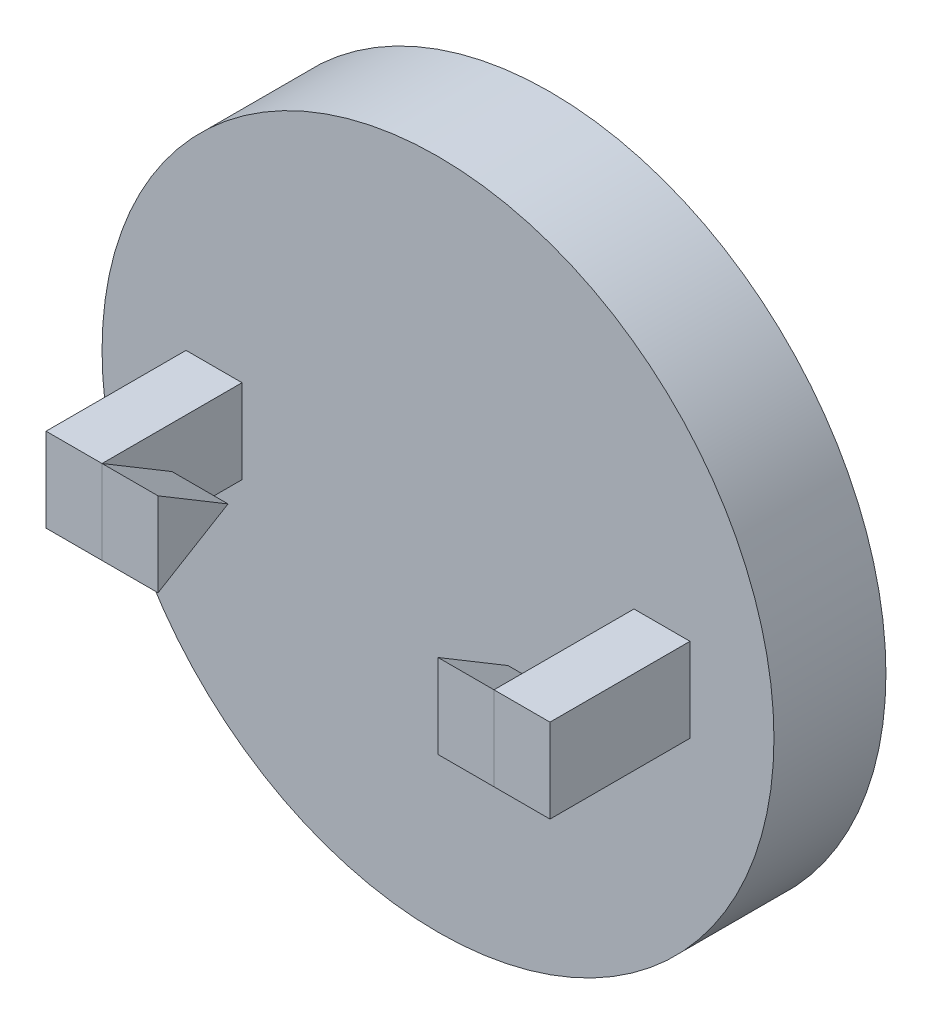
SolidWorks part; units mm, degrees
ref_plane "前视基准面" through (0, 0, 0) normal (0, 0, 1) x (1, 0, 0)
ref_plane "上视基准面" through (0, 0, 0) normal (0, 1, 0) x (1, 0, 0)
ref_plane "右视基准面" through (0, 0, 0) normal (1, 0, 0) x (0, 0, -1)
other "Configuration Table"
sketch "草图1" plane through (0, 0, 0) normal (0, 0, 1) x (1, 0, 0)
  circle A0 centre (0, 0) radius 60
  point P3 (0, 0)
extrude "凸台-拉伸1" add sketch "草图1" along normal mid plane 20
sketch "草图2" plane through (0, 0, 10) normal (0, 0, 1) x (1, 0, 0)
  line L1 (-45, 7.5) -> (-35, 7.5)
  line L2 (-45, 7.5) -> (-45, -7.5)
  line L3 (-45, -7.5) -> (-35, -7.5)
  line L4 (-35, 7.5) -> (-35, -7.5)
  line L5 (-45, 7.5) -> (-35, -7.5) construction
  line L6 (-45, -7.5) -> (-35, 7.5) construction
  point P0 (-40, 0)
  point P5 (0, 0)
  point P8 (-92.1211, -9.0222)
  dimension "D1" = 15
  dimension "D2" = 10
  dimension "D3" = 40
extrude "凸台-拉伸2" add sketch "草图2" along normal blind 25 separate body
sketch "草图4" plane through (-35, 0, 0) normal (1, 0, 0) x (0, 0, -1)
  line L9 (-10, -7.5) -> (-10, 7.5)
  line L10 (-10, 7.5) -> (-35, 7.5)
  line L11 (-35, 7.5) -> (-35, -7.5)
  line L12 (-35, -7.5) -> (-10, -7.5)
  line L14 (-10, 7.5) -> (-35, 7.5)
  line L16 (-35, -7.5) -> (-10, -7.5)
  line L17 (-10, -7.5) -> (-10, 7.5)
  line B0 (-35, -7.5) -> (-22.5, 0)
  line B1 (-35, 7.5) -> (-22.5, 0)
  line B2 (-35, -7.5) -> (-35, 7.5)
  line M14 (-35, 7.5) -> (-35, -7.5)
  dimension "D1" = 0
sketch_block_instance "块1-1"
sketch_block "块1"
extrude "凸台-拉伸3" add sketch "草图4" along normal blind 10 separate body contours B1 B0 M14
mirror "镜向1" about plane through (0, 0, 0) normal (1, 0, 0) of bodies 108 107
